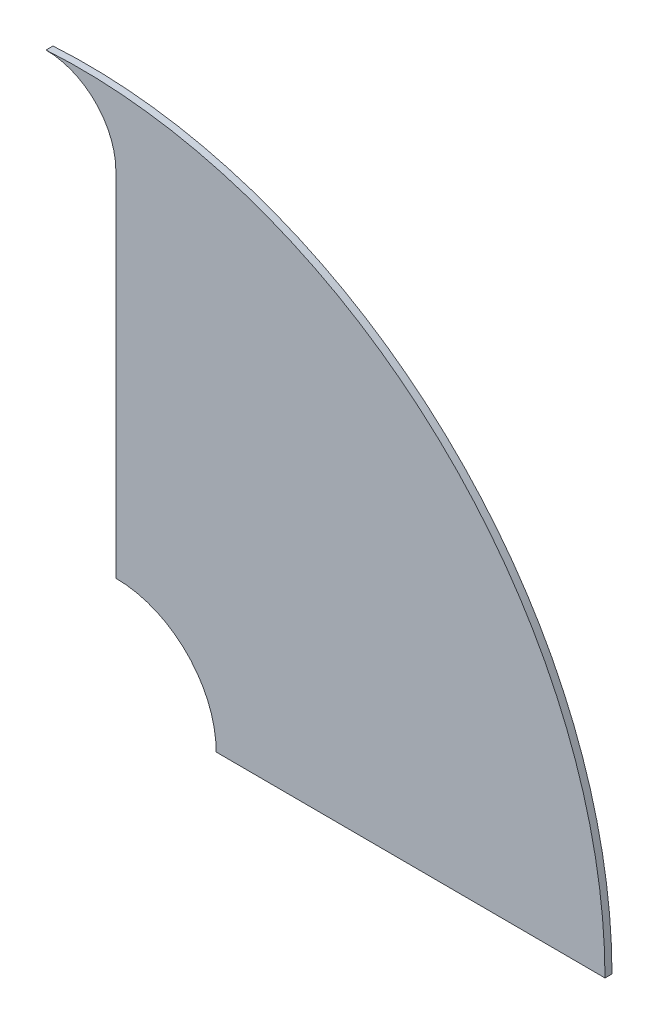
SolidWorks part; units mm, degrees
ref_plane "Front Plane" through (0, 0, 0) normal (0, 0, 1) x (1, 0, 0)
ref_plane "Top Plane" through (0, 0, 0) normal (0, 1, 0) x (1, 0, 0)
ref_plane "Right Plane" through (0, 0, 0) normal (1, 0, 0) x (0, 0, -1)
sketch "Sketch1" plane through (0, 0, 0) normal (0, 0, 1) x (1, 0, 0)
  line L0 (820.1756, -512.1087) -> (846.5688, -512.1087)
  line L4 (946.5688, -612.1087) -> (946.5688, -1116.8072)
  line L5 (1090.1781, -1260.4164) -> (1646.5688, -1262.2429)
  line L6 (946.5688, -1260.4164) -> (946.5688, -1262.2429)
  line L17 (946.5688, -1262.2429) -> (946.5688, -1260.4164)
  arc A2 (846.5688, -512.1087) -> (946.5688, -612.1087) centre (846.5688, -612.1087) cw
  arc A3 (846.5688, -512.1087) -> (1646.5688, -1262.2429) centre (894.8804, -1262.2429) cw
  arc A4 (1090.1781, -1260.4164) -> (946.5688, -1116.8072) centre (946.5688, -1260.4164) ccw
  point P0 (596.4549, -1260.4164)
extrude "Boss-Extrude2" add sketch "Sketch1" against normal blind 10
